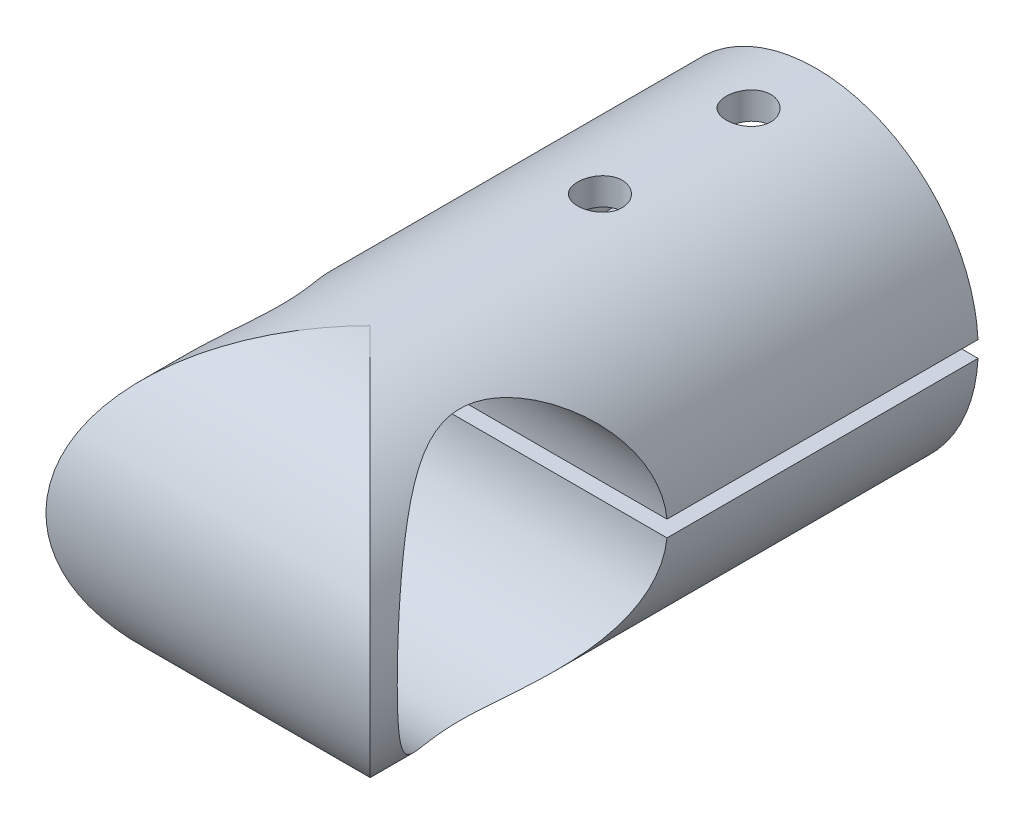
SolidWorks part; units mm, degrees
ref_plane "Plan de face" through (0, 0, 0) normal (0, 0, 1) x (1, 0, 0)
ref_plane "Plan de dessus" through (0, 0, 0) normal (0, 1, 0) x (1, 0, 0)
ref_plane "Plan de droite" through (0, 0, 0) normal (1, 0, 0) x (0, 0, -1)
sketch "Esquisse1" plane through (0, 0, 0) normal (0, 0, 1) x (1, 0, 0)
  circle A0 centre (0, 0) radius 10
  circle A1 centre (0, 0) radius 12
  dimension "D1" = 24
  dimension "D2" = 20
extrude "Boss.-Extru.1" add sketch "Esquisse1" along normal blind 21
sketch "Esquisse2" plane through (0, 0, 21) normal (0, 0, 1) x (1, 0, 0)
  circle A0 centre (0, 0) radius 12
  circle A1 centre (0, 0) radius 12 construction
extrude "Boss.-Extru.2" add sketch "Esquisse2" along normal blind 24
sketch "Esquisse3" plane through (0, 0, 0) normal (1, 0, 0) x (0, 0, -1)
  line L0 (-45, 0) -> (0, 0) construction
  line L1 (-45, 12) -> (-45, -12) construction
  line L2 (-45, -12) -> (0, -12) construction
  line L3 (-33, 12) -> (-45, 12)
  line L4 (-45, 12) -> (-50, 0)
  line L5 (-50, 0) -> (-45, -12)
  line L6 (-45, -12) -> (-33, -12)
  line L7 (0, -12) -> (0, 12) construction
  line L8 (0, 12) -> (-45, 12) construction
  line L9 (-23.018, 0.6) -> (0, 0.6)
  line L10 (0, 0.6) -> (0, -0.6)
  line L11 (0, -0.6) -> (-23.018, -0.6)
  circle A0 centre (-33, 0) radius 12 construction
  arc A1 (-33, 12) -> (-33, -12) centre (-33, 0) ccw
  circle A2 centre (-33, 0) radius 10 construction
  arc A3 (-23.018, 0.6) -> (-23.018, -0.6) centre (-33, 0) ccw
  point P21 (0, 0)
  point P28 (0, 0)
  dimension "D1" = 20
  dimension "D3" = 12
  dimension "D2" = 33
  dimension "D4" = 5
  dimension "D5" = 1.2
extrude "Enlèv. mat.-Extru.1" cut sketch "Esquisse3" against normal through all and the other way through all
sketch "Esquisse4" plane through (0, -0.6, 0) normal (0, 1, 0) x (1, 0, 0)
  line L0 (0, 0) -> (0, -16) construction
  line L1 (11.985, 0) -> (-11.985, 0) construction
  circle A0 centre (0, -16) radius 1.65
  circle A1 centre (0, -5) radius 1.65
  point P5 (0, -4.4342)
  point P7 (0, -17.7086)
  dimension "D1" = 3.3
  dimension "D2" = 5
  dimension "D3" = 16
extrude "Enlèv. mat.-Extru.2" cut sketch "Esquisse4" against normal through all and the other way through all
